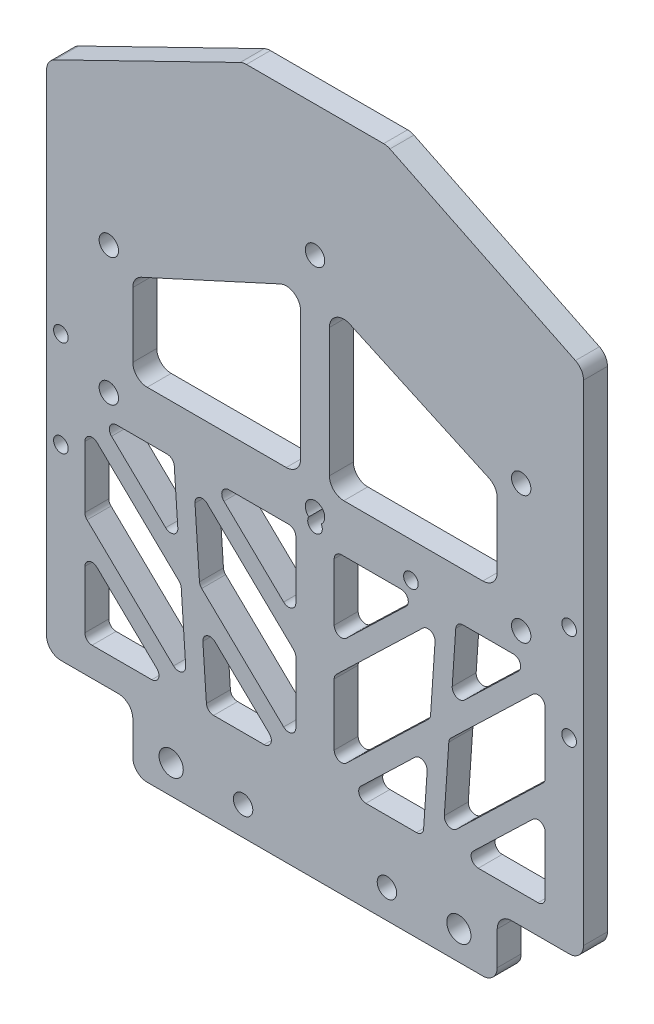
SolidWorks part; units mm, degrees
material "Thornel Mat VMA"
ref_plane "前视基准面" through (0, 0, 0) normal (0, 0, 1) x (1, 0, 0)
ref_plane "上视基准面" through (0, 0, 0) normal (0, 1, 0) x (1, 0, 0)
ref_plane "右视基准面" through (0, 0, 0) normal (1, 0, 0) x (0, 0, -1)
other "Configuration Table"
sketch "草图1" plane through (0, 0, 0) normal (0, 0, 1) x (1, 0, 0)
  line L1 (-56, -70) -> (56, -70)
  line L2 (-56, -70) -> (-56, 70)
  line L3 (-56, 70) -> (56, 70)
  line L4 (56, -70) -> (56, 70)
  line L5 (-56, -70) -> (56, 70) construction
  line L6 (-56, 70) -> (56, -70) construction
  point P0 (0, 0)
  dimension "D1" = 112
  dimension "D2" = 140
extrude "凸台-拉伸1" add sketch "草图1" along normal mid plane 5
sketch "草图2" plane through (0, 0, 2.5) normal (0, 0, 1) x (1, 0, 0)
  circle A0 centre (0, 13.35) radius 33.35 construction
  circle A1 centre (0, 13.35) radius 33.35 construction
  circle A2 centre (0, 13.35) radius 34.35
  dimension "D1" = 1
extrude "切除-拉伸1" [suppressed] cut sketch "草图2" against normal up to surface (5 mm away)
sketch "草图3" plane through (0, 0, 2.5) normal (0, 0, 1) x (1, 0, 0)
  line L0 (-15, 70) -> (-56, 50)
  line L1 (56, 70) -> (-56, 70) construction
  line L2 (-56, 70) -> (-56, -70) construction
  line L3 (-56, 50) -> (-56, 70)
  line L4 (-56, 70) -> (-15, 70)
  line L5 (0, 0) -> (0, 70) construction
  line L6 (56, 70) -> (15, 70)
  line L7 (56, 50) -> (56, 70)
  line L8 (15, 70) -> (56, 50)
  dimension "D1" = 20
  dimension "D2" = 15
extrude "切除-拉伸2" cut sketch "草图3" against normal up to surface (5 mm away) up to face at (0, 0, -2.5)
sketch "草图4" plane through (0, 0, 2.5) normal (0, 0, 1) x (1, 0, 0)
  circle A1 centre (0, -3.65) radius 2.025
  circle A2 centre (0, -3.65) radius 2.025
  circle A3 centre (43, -3.65) radius 2.025
  circle A4 centre (43, -3.65) radius 2.025
  circle A5 centre (-43, -3.65) radius 2.025
  circle A6 centre (-43, -3.65) radius 2.025
  circle A7 centre (-43, 23) radius 2.025
  circle A8 centre (-43, 23) radius 2.025
  circle A9 centre (0, 42.6963) radius 2.025
  circle A10 centre (0, 42.6963) radius 2.025
  circle A11 centre (43, 23) radius 2.025
  circle A12 centre (43, 23) radius 2.025
  dimension "D1" = 0
  dimension "D2" = 0
  dimension "D3" = 0
  dimension "D4" = 0
  dimension "D5" = 0
  dimension "D6" = 0
extrude "切除-拉伸3" cut sketch "草图4" against normal blind 10
sketch "草图5" [suppressed] plane through (0, 0, 2.5) normal (0, 0, 1) x (1, 0, 0)
  circle A1 centre (-43, 18.35) radius 2.025
  circle A2 centre (-43, 18.35) radius 2.025
  circle A3 centre (19.6418, 56.4983) radius 2.025
  circle A4 centre (19.6418, 56.4983) radius 2.025
  circle A5 centre (0, 64.6963) radius 2.025
  circle A6 centre (0, 64.6963) radius 2.025
  circle A7 centre (-21.5974, 46.2434) radius 2.025
  circle A8 centre (-21.5974, 46.2434) radius 2.025
  circle A9 centre (-43, 50.7783) radius 2.025
  circle A10 centre (-43, 50.7783) radius 2.025
  dimension "D1" = 0
  dimension "D2" = 0
  dimension "D3" = 0
  dimension "D4" = 0
  dimension "D5" = 0
extrude "切除-拉伸4" [suppressed] cut sketch "草图5" against normal blind 10
sketch "草图6" plane through (0, 0, -2.5) normal (0, 0, -1) x (-1, 0, 0)
  line L1 (56, -70) -> (38, -70)
  line L2 (56, -70) -> (56, -57)
  line L3 (56, -57) -> (38, -57)
  line L4 (38, -70) -> (38, -57)
  dimension "D1" = 13
  dimension "D2" = 18
extrude "切除-拉伸5" cut sketch "草图6" against normal blind 10
mirror "镜向2" about plane through (0, 0, 0) normal (1, 0, 0) of "切除-拉伸5"
sketch "草图7" plane through (0, 0, 2.5) normal (0, 0, 1) x (1, 0, 0)
  line L0 (0, 37.1967) -> (-38, 19.7907)
  line L1 (-38, 19.7907) -> (-38, 1.35)
  line L2 (-38, 1.35) -> (38, 1.35)
  line L3 (38, 1.35) -> (38, 19.7907)
  line L4 (38, 19.7907) -> (0, 37.1967)
  line L6 (0, 37.1967) -> (0, 1.35) construction
  line L7 (0, 1.35) -> (0, 0) construction
  line L8 (0, 42.6963) -> (-43, 23) construction
  line L9 (0, 42.6963) -> (43, 23) construction
  line L10 (-3, 37.1967) -> (-3, 1.35)
  line L11 (3, 37.1967) -> (3, 1.35)
  line L12 (-3, 37.1967) -> (3, 37.1967)
  line L13 (-3, 1.35) -> (3, 1.35)
  circle A0 centre (43, -3.65) radius 2.025 construction
  dimension "D1" = 5
  dimension "D2" = 5
  dimension "D3" = 5
  dimension "D4" = 3
  dimension "D5" = 3
extrude "切除-拉伸6" cut sketch "草图7" against normal up to surface (5 mm away) contours L10 L0 L1 L2 | L4 L11 L2 L3 up to face at (40.975, -3.65, -2.5)
fillet "圆角1" radius 3 8 edges at (3, 35.8226, 0) (38, 19.7907, 0) (38, 1.35, 0) (3, 1.35, 0) (-3, 35.8226, 0) (-38, 19.7907, 0) (-38, 1.35, 0) (-3, 1.35, 0)
sketch "草图8" plane through (0, 0, -2.5) normal (0, 0, -1) x (-1, 0, 0)
  circle A0 centre (-53, -18) radius 1.25 construction
  circle A1 centre (-53, 2) radius 1.25 construction
  circle A2 centre (-53, -18) radius 1.25 construction
  circle A3 centre (-53, 2) radius 1.25 construction
  circle A4 centre (-53, 2) radius 1.525
  circle A5 centre (-53, -18) radius 1.525
  dimension "D1" = 3.05
extrude "切除-拉伸7" cut sketch "草图8" against normal up to surface (5 mm away) up to face at (-20.7692, 14.3822, 2.5)
mirror "镜向3" about plane through (0, 0, 0) normal (1, 0, 0) of "切除-拉伸7"
sketch "草图9" [suppressed] plane through (0, 0, 2.5) normal (0, 0, 1) x (1, 0, 0)
  circle A0 centre (53, 2) radius 1.25 construction
  circle A1 centre (53, -18) radius 1.25 construction
  circle A2 centre (53, 2) radius 1.25 construction
  circle A3 centre (53, -18) radius 1.25 construction
  circle A4 centre (53, 2) radius 1.525
  circle A5 centre (53, -18) radius 1.525
  dimension "D1" = 3.05
extrude "切除-拉伸8" [suppressed] cut sketch "草图9" against normal blind 40
mirror "镜向4" [suppressed] about plane through (0, 0, 0) normal (1, 0, 0)
sketch "草图10" plane through (0, 0, 2.5) normal (0, 0, 1) x (1, 0, 0)
  circle A0 centre (-30, -64) radius 2 construction
  circle A1 centre (30, -64) radius 2 construction
  circle A2 centre (-30, -64) radius 2 construction
  circle A3 centre (30, -64) radius 2 construction
  circle A4 centre (-30, -64) radius 2.525
  circle A5 centre (30, -64) radius 2.525
  dimension "D1" = 5.05
extrude "切除-拉伸9" cut sketch "草图10" against normal blind 40
fillet "圆角2" [suppressed] radius 3
fillet "圆角3" radius 3 10 edges at (38, -57, 0) (38, -70, 0) (-56, -57, 0) (-56, 50, 0) (-15, 70, 0) (15, 70, 0) (56, 50, 0) (56, -57, 0) (-38, -57, 0) (-38, -70, 0)
sketch "草图11" plane through (0, 0, -2.5) normal (0, 0, -1) x (-1, 0, 0)
  line L0 (0, 70) -> (0, -70) construction
  line L1 (-14.3073, 70) -> (14.3073, 70) construction
  line L2 (35, -70) -> (-35, -70) construction
  line L3 (-48, -8.65) -> (-48, -51)
  line L4 (-48, -51) -> (-4, -51)
  line L5 (-4, -51) -> (-4, -8.65)
  line L6 (-4, -8.65) -> (-48, -8.65)
  line L7 (-53, -57) -> (-41, -57) construction
  line L8 (-4, -51) -> (-48, -8.65) construction
  line L9 (-2.6131, -49.559) -> (-46.6131, -7.209)
  line L10 (-5.3869, -52.441) -> (-49.3869, -10.091)
  line L11 (-2.6131, -49.559) -> (-5.3869, -52.441)
  line L12 (-46.6131, -7.209) -> (-49.3869, -10.091)
  circle A0 centre (-53, -18) radius 1.525 construction
  circle A1 centre (-43, -3.65) radius 2.025 construction
  dimension "D1" = 5
  dimension "D2" = 5
  dimension "D3" = 6
  dimension "D4" = 8
  dimension "D5" = 2
  dimension "D6" = 2
extrude "切除-拉伸10" cut sketch "草图11" against normal blind 78 contours L4 L10 L3 | L9 L5 L6
sketch "草图12" plane through (0, 0, -2.5) normal (0, 0, -1) x (-1, 0, 0)
  line L0 (-24.558, -8.65) -> (-4, -28.437) construction
  line L1 (-4, -8.65) -> (-45.1159, -8.65) construction
  line L2 (-4, -48.2241) -> (-4, -8.65) construction
  line L3 (-48, -31.213) -> (-27.442, -51) construction
  line L4 (-48, -11.4259) -> (-48, -51) construction
  line L5 (-48, -51) -> (-6.8841, -51) construction
  line L6 (-27.442, -8.65) -> (-4, -31.213)
  line L7 (-49.3869, -32.6539) -> (-28.829, -52.441)
  line L8 (-23.171, -7.209) -> (-2.6131, -26.9961)
  line L9 (-48, -28.437) -> (-24.558, -51)
  line L10 (-25.9449, -10.091) -> (-5.3869, -29.878) construction
  line L11 (-46.6131, -29.772) -> (-26.0551, -49.559) construction
  line L12 (-2.6131, -26.9961) -> (-4, -31.213)
  line L13 (-24.558, -51) -> (-28.829, -52.441)
  line L14 (-48, -28.437) -> (-49.3869, -32.6539)
  line L15 (-23.171, -7.209) -> (-27.442, -8.65)
  dimension "D1" = 2
  dimension "D2" = 2
extrude "凸台-拉伸2" add sketch "草图12" against normal up to surface (5 mm away) up to face at (0, -12.6661, 2.5)
sketch "草图13" plane through (0, 0, -2.5) normal (0, 0, -1) x (-1, 0, 0)
  line L0 (-27.442, -8.65) -> (-24.558, -51) construction
  line L1 (-29.4467, -8.65) -> (-26.5534, -51.1359)
  line L2 (-25.4466, -8.5141) -> (-22.5533, -51)
  line L3 (-29.4374, -8.7859) -> (-26.5534, -51.1359) construction
  line L4 (-27.442, -8.65) -> (-45.1159, -8.65) construction
  line L5 (-25.4466, -8.5141) -> (-22.5626, -50.8641) construction
  line L6 (-24.558, -51) -> (-6.8841, -51) construction
  line L7 (-22.5533, -51) -> (-26.5534, -51.1359)
  line L8 (-29.4467, -8.65) -> (-25.4466, -8.5141)
  dimension "D1" = 2
  dimension "D2" = 2
extrude "凸台-拉伸3" add sketch "草图13" against normal up to surface (5 mm away) up to face at (31.8605, -35.4657, 2.5)
mirror "镜向5" about plane through (0, 0, 0) normal (1, 0, 0) of "凸台-拉伸3", "凸台-拉伸2", "切除-拉伸10"
fillet "圆角4" radius 1.5 40 edges at (-48, -51, 0) (-30.3261, -51, 0) (-48, -33.9889, 0) (-4, -8.65, 0) (-21.6739, -8.65, 0) (-4, -25.6611, 0) (21.6739, -8.65, 0) (4, -8.65, 0) (4, -25.6611, 0) (30.3261, -51, 0) (48, -51, 0) (48, -33.9889, 0) (26.7032, -48.9352, 0) (48, -28.437, 0) (48, -11.4259, 0) (27.9429, -30.7308, 0) (25.2968, -10.7148, 0) (4, -31.213, 0) (24.0571, -28.9192, 0) (28.3475, -24.7896, 0) (45.1159, -8.65, 0) (29.4467, -8.65, 0) (23.6525, -34.8604, 0) (6.8841, -51, 0) (-48, -11.4259, 0) (-48, -28.437, 0) (-26.7032, -48.9352, 0) (-27.9429, -30.7308, 0) (-4, -48.2241, 0) (-4, -31.213, 0) (-25.2968, -10.7148, 0) (-24.0571, -28.9192, 0) (-45.1159, -8.65, 0) (-28.3475, -24.7896, 0) (-29.4467, -8.65, 0) (-6.8841, -51, 0) (-23.6525, -34.8604, 0) (-22.5533, -51, 0) (22.5533, -51, 0) (4, -48.2241, 0)
sketch "草图14" [suppressed] plane through (0, 0, -2.5) normal (0, 0, -1) x (-1, 0, 0)
  line L0 (0, 13.35) -> (-56, 13.35) construction
  line L1 (-56, -54) -> (-56, 48.1255) construction
  line L2 (-48, 3.35) -> (-48, -49)
  line L3 (-48, -49) -> (-4, -49)
  line L4 (-4, -49) -> (-4, -28.8107)
  line L5 (-48, 3.35) -> (-41.1524, 3.35)
  line L6 (-53, -57) -> (-41, -57) construction
  line L7 (0, 0) -> (0, -70) construction
  line L8 (35, -70) -> (-35, -70) construction
  arc A0 (-41.1524, 3.35) -> (-4, -28.8107) centre (0, 13.35) ccw
  circle A1 centre (0, 13.35) radius 34.35 construction
  circle A2 centre (-53, 2) radius 1.525 construction
  dimension "D1" = 8
  dimension "D2" = 5
  dimension "D3" = 10
  dimension "D4" = 8
  dimension "D5" = 8
extrude "切除-拉伸11" [suppressed] cut sketch "草图14" against normal up to surface (5 mm away)
mirror "镜向6" [suppressed] about plane through (0, 0, 0) normal (1, 0, 0)
sketch "草图15" [suppressed] plane through (0, 0, -2.5) normal (0, 0, -1) x (-1, 0, 0)
  line L0 (-27.7176, -18.6697) -> (-48, -49) construction
  line L1 (-48, -49) -> (-4, -49) construction
  line L2 (-48, 3.35) -> (-48, -49) construction
  line L3 (-29.2144, -17.3101) -> (-49.6625, -47.8882)
  line L4 (-26.055, -19.7814) -> (-46.3375, -50.1118)
  line L5 (-29.3801, -17.5579) -> (-49.6625, -47.8882) construction
  line L6 (-49.6625, -47.8882) -> (-46.3375, -50.1118)
  line L7 (-26.055, -19.7814) -> (-29.2144, -17.3101)
  arc A0 (-41.1524, 3.35) -> (-4, -28.8107) centre (0, 13.35) ccw construction
  dimension "D1" = 2
  dimension "D2" = 2
extrude "凸台-拉伸4" [suppressed] add sketch "草图15" against normal up to surface (5 mm away)
mirror "镜向7" [suppressed] about plane through (0, 0, 0) normal (1, 0, 0)
sketch "草图16" [suppressed] plane through (0, 0, -2.5) normal (0, 0, -1) x (-1, 0, 0)
  line L0 (-26.167, -19.9488) -> (-14, -49) construction
  line L1 (-45.594, -49) -> (-4, -49) construction
  line L2 (-28.0117, -20.7214) -> (-15.8447, -49.7726)
  line L3 (-24.3222, -19.1762) -> (-11.8317, -49)
  line L4 (-24.3222, -19.1762) -> (-12.1553, -48.2274) construction
  line L5 (-11.8317, -49) -> (-15.8447, -49.7726)
  line L6 (-24.3222, -19.1762) -> (-28.0117, -20.7214)
  dimension "D1" = 10
  dimension "D2" = 2
  dimension "D3" = 2
extrude "凸台-拉伸5" [suppressed] add sketch "草图16" against normal up to surface (5 mm away)
mirror "镜向8" [suppressed] about plane through (0, 0, 0) normal (1, 0, 0)
fillet "圆角5" [suppressed] radius 1.5
sketch "草图17" [suppressed] plane through (0, 0, -2.5) normal (0, 0, -1) x (-1, 0, 0)
  line L0 (35, -70) -> (-35, -70) construction
  line L1 (-24, -54) -> (24, -54)
  line L2 (-24, -54) -> (-24, -65)
  line L3 (-24, -65) -> (24, -65)
  line L4 (24, -54) -> (24, -65)
  line L5 (-42.7865, -49) -> (-18.4228, -49) construction
  circle A0 centre (30, -64) radius 2.525 construction
  circle A1 centre (-30, -64) radius 2.525 construction
  dimension "D1" = 6
  dimension "D2" = 6
  dimension "D3" = 5
  dimension "D4" = 5
extrude "切除-拉伸12" [suppressed] cut sketch "草图17" against normal up to surface (5 mm away)
fillet "圆角6" [suppressed] radius 2
sketch "草图19" [suppressed] plane through (0, 0, 2.5) normal (0, 0, 1) x (1, 0, 0)
  line L0 (42.1607, 9.35) -> (48, 9.35)
  line L1 (48, 9.35) -> (48, 45.0014)
  line L2 (48, 45.0014) -> (25.955, 55.755)
  line L3 (25.955, 55.755) -> (22.7075, 49.0976)
  line L4 (15.6226, 69.6963) -> (54.3153, 50.8218) construction
  line L5 (48, 1.85) -> (48, -40.4606) construction
  line L6 (42.3152, 3.35) -> (46.5, 3.35) construction
  arc A0 (42.1607, 9.35) -> (22.7075, 49.0976) centre (0, 13.35) ccw
  circle A1 centre (19.6418, 56.4983) radius 2.025 construction
  dimension "D1" = 84.7
  dimension "D2" = 8
  dimension "D3" = 6
  dimension "D4" = 6
extrude "切除-拉伸13" [suppressed] cut sketch "草图19" against normal up to surface (5 mm away)
fillet "圆角7" [suppressed] radius 2
sketch "草图20" [suppressed] plane through (0, 0, -2.5) normal (0, 0, -1) x (-1, 0, 0)
  line L0 (27.2384, 45.7783) -> (48, 45.7783)
  line L1 (48, 45.7783) -> (48, 24.35)
  line L2 (48, 24.35) -> (40.8965, 24.35)
  line L3 (48, 1.85) -> (48, -40.4606) construction
  arc A0 (40.8965, 24.35) -> (27.2384, 45.7783) centre (0, 13.35) ccw
  circle A1 centre (43, 18.35) radius 2.025 construction
  circle A2 centre (43, 50.7783) radius 2.025 construction
  dimension "D1" = 84.7
  dimension "D2" = 6
  dimension "D3" = 5
extrude "切除-拉伸14" [suppressed] cut sketch "草图20" against normal up to surface (5 mm away)
fillet "圆角8" [suppressed] radius 2
sketch "草图21" plane through (0, 0, -2.5) normal (0, 0, -1) x (-1, 0, 0)
  line L0 (-20, -3) -> (-25.8222, -3)
  line L1 (-24.0964, -28.3417) -> (-25.0327, -14.5933) construction
  line L2 (-25.8222, -3) -> (-25.4136, -9)
  line L3 (-25.4136, -9) -> (-20, -9)
  circle A0 centre (0, -6) radius 1.25 construction
  circle A1 centre (0, -6) radius 1.25 construction
  circle A2 centre (-20, -6) radius 1.25 construction
  circle A3 centre (-20, -6) radius 1.25 construction
  arc A4 (-20, -9) -> (-20, -3) centre (-20, -6) ccw
  dimension "D1" = 6
extrude "凸台-拉伸6" add sketch "草图21" against normal up to surface (5 mm away) up to face at (-18.0036, -46.0154, 2.5)
sketch "草图22" plane through (0, 0, -2.5) normal (0, 0, -1) x (-1, 0, 0)
  circle A0 centre (0, -6) radius 1.525
  circle A1 centre (-20, -6) radius 1.525
  dimension "D1" = 3.05
extrude "切除-拉伸15" cut sketch "草图22" against normal up to surface (5 mm away) up to face at (-18.0036, -46.0154, 2.5)
fillet "圆角9" [suppressed] radius 3
sketch "草图23" [suppressed] plane through (0, 0, -2.5) normal (0, 0, -1) x (-1, 0, 0)
  circle A0 centre (-26.4104, 39.7604) radius 2.025 construction
  circle A1 centre (-37.35, 13.35) radius 2.025 construction
  circle A2 centre (-26.4104, -13.0604) radius 2.025 construction
  circle A3 centre (26.4104, -13.0604) radius 2.025 construction
  circle A4 centre (37.35, 13.35) radius 2.025 construction
  circle A5 centre (26.4104, 39.7604) radius 2.025 construction
  circle A6 centre (0, 50.7) radius 2.025 construction
  circle A7 centre (-26.4104, 39.7604) radius 2.025
  circle A8 centre (-37.35, 13.35) radius 2.025
  circle A9 centre (-26.4104, -13.0604) radius 2.025
  circle A10 centre (26.4104, -13.0604) radius 2.025
  circle A11 centre (37.35, 13.35) radius 2.025
  circle A12 centre (26.4104, 39.7604) radius 2.025
  circle A13 centre (0, 50.7) radius 2.025
extrude "切除-拉伸16" [suppressed] cut sketch "草图23" against normal blind 66
sketch "草图24" plane through (0, 0, 2.5) normal (0, 0, 1) x (1, 0, 0)
  line L0 (-30, -64) -> (30, -64) construction
  line L1 (0, -64) -> (0, -76.4268) construction
  circle A0 centre (-15, -64) radius 2.025
  circle A1 centre (15, -64) radius 2.025
  dimension "D2" = 4.05
  dimension "D1" = 30
extrude "切除-拉伸17" cut sketch "草图24" against normal blind 10
